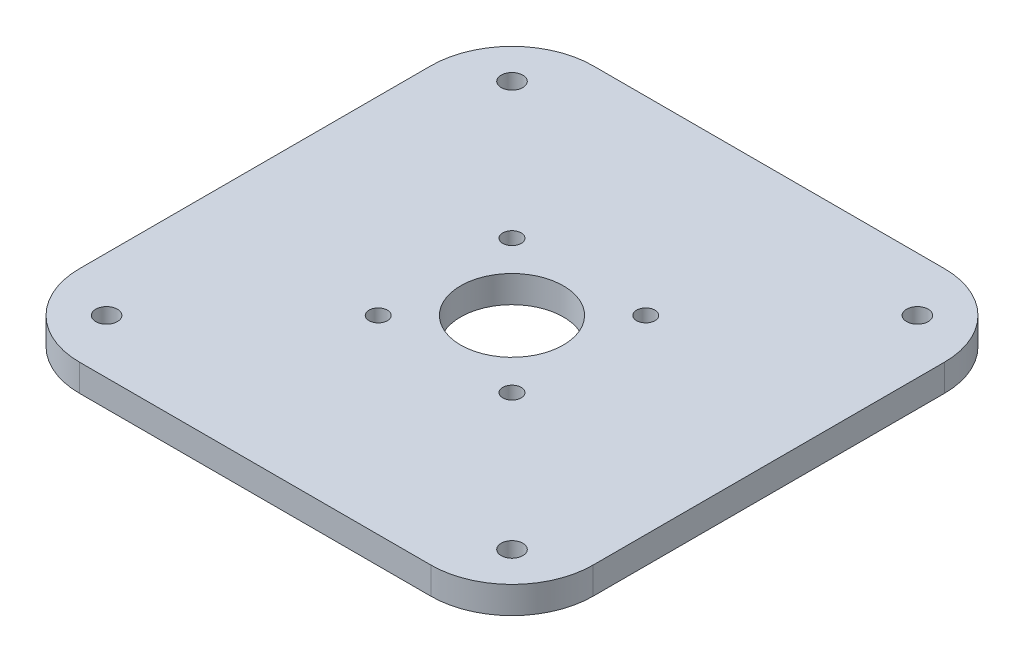
SolidWorks part; units mm, degrees
ref_plane "前视基准面" through (0, 0, 0) normal (0, 0, 1) x (1, 0, 0)
ref_plane "上视基准面" through (0, 0, 0) normal (0, 1, 0) x (1, 0, 0)
ref_plane "右视基准面" through (0, 0, 0) normal (1, 0, 0) x (0, 0, -1)
sketch "Sketch2" plane through (0, 0, 0) normal (0, 1, 0) x (1, 0, 0)
  line L1 (95, -95) -> (-95, -95)
  line L2 (95, -95) -> (95, 95)
  line L3 (95, 95) -> (-95, 95)
  line L4 (-95, -95) -> (-95, 95)
  line L5 (95, -95) -> (-95, 95) construction
  line L6 (95, 95) -> (-95, -95) construction
  point P0 (0, 0)
  dimension "D1" = 190
  dimension "D2" = 190
extrude "Extrude1" add sketch "Sketch2" along normal blind 10
sketch "Sketch3" plane through (0, 10, 0) normal (0, 1, 0) x (1, 0, 0)
  line L0 (0, 75) -> (0, -75) construction
  line L1 (75, -75) -> (-75, -75) construction
  line L2 (75, -75) -> (75, 75) construction
  line L3 (75, 75) -> (-75, 75) construction
  line L4 (-75, -75) -> (-75, 75) construction
  line L5 (75, -75) -> (-75, 75) construction
  line L6 (75, 75) -> (-75, -75) construction
  line L7 (-75, 0) -> (75, 0) construction
  circle A0 centre (0, 0) radius 19
  circle A1 centre (-75, 75) radius 4
  circle A2 centre (75, 75) radius 4
  circle A3 centre (75, -75) radius 4
  circle A4 centre (-75, -75) radius 4
  dimension "D3" = 8
  dimension "D4" = 38
  dimension "D1" = 150
  dimension "D2" = 150
extrude "Extrude2" cut sketch "Sketch3" against normal blind 10
fillet "Fillet1" radius 30 4 edges at (-95, 5, 95) (95, 5, 95) (95, 5, -95) (-95, 5, -95)
sketch "Sketch4" plane through (0, 10, 0) normal (0, 1, 0) x (1, 0, 0)
  line L1 (24.7487, -24.7487) -> (-24.7487, -24.7487) construction
  line L2 (24.7487, -24.7487) -> (24.7487, 24.7487) construction
  line L3 (24.7487, 24.7487) -> (-24.7487, 24.7487) construction
  line L4 (-24.7487, -24.7487) -> (-24.7487, 24.7487) construction
  line L5 (24.7487, -24.7487) -> (-24.7487, 24.7487) construction
  line L6 (24.7487, 24.7487) -> (-24.7487, -24.7487) construction
  circle A0 centre (0, 0) radius 35 construction
  dimension "D1" = 70
hole_wizard "M8 Tapped Hole1" positions "3DSketch1" profile "Sketch5" tap size "M8" standard "GB"
sketch3d "3DSketch1"
  point P0 (-24.7487, 10, -24.7487)
  point P3 (24.7487, 10, -24.7487)
  point P6 (-24.7487, 10, 24.7487)
  point P9 (24.7487, 10, 24.7487)
sketch "Sketch5" plane through (-24.7487, 10, -24.7487) normal (1, 0, 0) x (0, 0, 1)
  line L0 (0, 0) -> (0, 21.7929)
  line L1 (0, 21.7929) -> (3.4, 19.75)
  line L2 (3.4, 19.75) -> (3.4, 0)
  line L5 (3.4, 0) -> (0, 0)
  line L10 (0, 21.7929) -> (-3.4, 19.75) construction
  line L11 (0, -6.35) -> (0, 107.95) construction
  dimension "螺纹孔钻头直径" = 6.8
  dimension "螺纹孔钻头深度" = 19.75
  dimension "导头角度" = 118
sketch "Sketch6" plane through (0, 10, 0) normal (0, 1, 0) x (1, 0, 0)
  circle A0 centre (0, 0) radius 25
  dimension "D1" = 50
